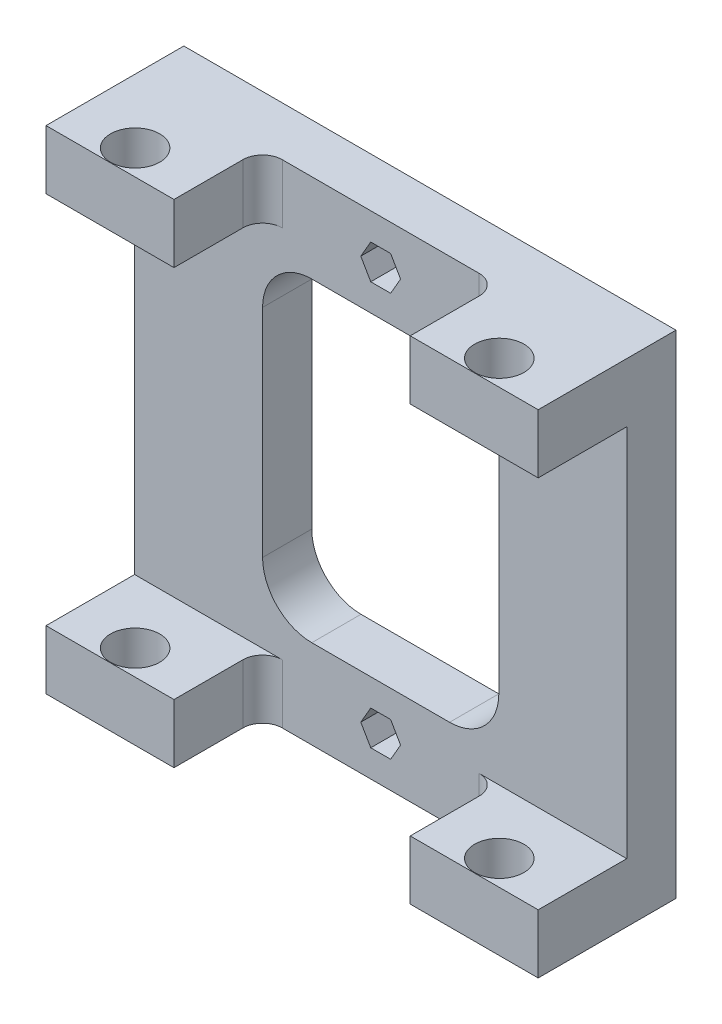
SolidWorks part; units mm, degrees
ref_plane "Alzado" through (0, 0, 0) normal (0, 0, 1) x (1, 0, 0)
ref_plane "Planta" through (0, 0, 0) normal (0, 1, 0) x (1, 0, 0)
ref_plane "Vista lateral" through (0, 0, 0) normal (1, 0, 0) x (0, 0, -1)
sketch "Croquis1" plane through (0, 0, 0) normal (0, 0, 1) x (1, 0, 0)
  line L1 (25, -25) -> (-25, -25)
  line L2 (25, -25) -> (25, 25)
  line L3 (25, 25) -> (-25, 25)
  line L4 (-25, -25) -> (-25, 25)
  line L5 (25, -25) -> (-25, 25) construction
  line L6 (25, 25) -> (-25, -25) construction
  line L7 (7, -16) -> (-7, -16)
  line L8 (12, -11) -> (12, 11)
  line L9 (7, 16) -> (-7, 16)
  line L10 (-12, -11) -> (-12, 11)
  line L11 (12, -16) -> (-12, 16) construction
  line L12 (12, 16) -> (-12, -16) construction
  arc A0 (12, 11) -> (7, 16) centre (7, 11) ccw
  arc A1 (7, -16) -> (12, -11) centre (7, -11) ccw
  arc A2 (-7, -16) -> (-12, -11) centre (-7, -11) cw
  arc A3 (-7, 16) -> (-12, 11) centre (-7, 11) ccw
  point P0 (0, 0)
  point P6 (0, 0)
  dimension "D5" = 5
  dimension "D1" = 50
  dimension "D2" = 50
  dimension "D3" = 13
  dimension "D4" = 9
extrude "Saliente-Extruir1" add sketch "Croquis1" along normal blind 5
sketch "Croquis2" plane through (0, 0, 5) normal (0, 0, 1) x (1, 0, 0)
  line L0 (12, 25) -> (12, 19)
  line L1 (-25, 25) -> (-12, 25)
  line L2 (-25, 25) -> (-25, 19)
  line L3 (-25, 19) -> (-12, 19)
  line L4 (-12, 25) -> (-12, 19)
  line L5 (12, 25) -> (25, 25)
  line L6 (25, 25) -> (25, 19)
  line L7 (12, 19) -> (25, 19)
  line L8 (12, -19) -> (12, -25)
  line L9 (12, -19) -> (25, -19)
  line L10 (25, -19) -> (25, -25)
  line L11 (12, -25) -> (25, -25)
  line L12 (-25, -19) -> (-25, -25)
  line L13 (-25, -19) -> (-12, -19)
  line L14 (-12, -19) -> (-12, -25)
  line L15 (-25, -25) -> (-12, -25)
  dimension "D1" = 13
  dimension "D2" = 6
  dimension "D5" = 38
  dimension "D6" = 24
  dimension "D3" = 2
  dimension "D4" = 2
extrude "Saliente-Extruir2" add sketch "Croquis2" along normal blind 9
sketch "Croquis3" plane through (0, 25, 0) normal (0, 1, 0) x (1, 0, 0)
  line L0 (0, 0) -> (0, -14) construction
  line L1 (25, 0) -> (-25, 0) construction
  line L2 (-12, -14) -> (-25, -14) construction
  line L3 (-18.5, -14) -> (-18.5, 0) construction
  circle A0 centre (-18.5, -11.45) radius 2.5
  circle A2 centre (18.5, -11.45) radius 2.5
  dimension "D1" = 5
  dimension "D2" = 2.55
extrude "Cortar-Extruir5" cut sketch "Croquis3" against normal through all
fillet "Redondeo1" radius 2 4 edges at (12, -22, 5) (-12, -22, 5) (12, 22, 5) (-12, 22, 5)
sketch "Croquis4" plane through (0, 0, 5) normal (0, 0, 1) x (1, 0, 0)
  line L0 (0, 16) -> (0, 25) construction
  line L1 (-1.0104, 18.75) -> (1.0104, 18.75)
  line L2 (1.0104, 18.75) -> (2.0207, 20.5)
  line L3 (2.0207, 20.5) -> (1.0104, 22.25)
  line L4 (1.0104, 22.25) -> (-1.0104, 22.25)
  line L5 (-1.0104, 22.25) -> (-2.0207, 20.5)
  line L6 (-2.0207, 20.5) -> (-1.0104, 18.75)
  line L7 (7, 16) -> (-7, 16) construction
  line L8 (10, 25) -> (-10, 25) construction
  line L9 (0, 0) -> (-25, 0) construction
  line L10 (-25, 19) -> (-25, -19) construction
  line L11 (-2.0207, -20.5) -> (-1.0104, -18.75)
  line L12 (-1.0104, -22.25) -> (-2.0207, -20.5)
  line L13 (1.0104, -22.25) -> (-1.0104, -22.25)
  line L14 (2.0207, -20.5) -> (1.0104, -22.25)
  line L15 (1.0104, -18.75) -> (2.0207, -20.5)
  line L16 (-1.0104, -18.75) -> (1.0104, -18.75)
  circle A0 centre (0, 20.5) radius 1.75 construction
  point P16 (0, 20.5)
  dimension "D1" = 3.5
extrude "Cortar-Extruir6" cut sketch "Croquis4" against normal blind 4
sketch "Croquis5" plane through (0, 0, 1) normal (0, 0, 1) x (1, 0, 0)
  line L0 (0, 25) -> (0, 16) construction
  line L1 (10, 25) -> (-10, 25) construction
  line L2 (7, 16) -> (-7, 16) construction
  line L3 (0, 0) -> (-25, 0) construction
  line L4 (-25, 19) -> (-25, -19) construction
  circle A0 centre (0, 20.5) radius 1.5
  circle A1 centre (0, -20.5) radius 1.5
  dimension "D1" = 3
extrude "Cortar-Extruir7" cut sketch "Croquis5" against normal blind 4
